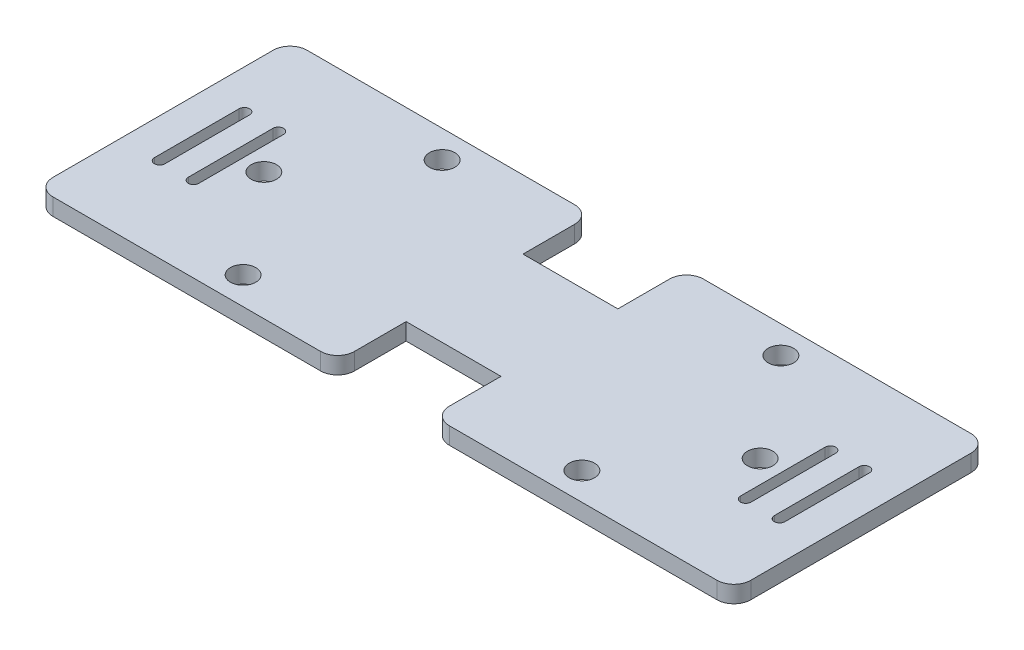
SolidWorks part; units mm, degrees
material "Thornel Mat VMA"
ref_plane "前视基准面" through (0, 0, 0) normal (0, 0, 1) x (1, 0, 0)
ref_plane "上视基准面" through (0, 0, 0) normal (0, 1, 0) x (1, 0, 0)
ref_plane "右视基准面" through (0, 0, 0) normal (1, 0, 0) x (0, 0, -1)
other "Configuration Table"
sketch "草图1" plane through (0, 0, 0) normal (0, 1, 0) x (1, 0, 0)
  line L0 (-5.6, 6.9) -> (-5.6, 13)
  line L1 (-39.2, -15) -> (-7.6, -15)
  line L2 (-41.2, -13) -> (-41.2, 13)
  line L3 (-39.2, 15) -> (-7.6, 15)
  line L4 (41.2, -13) -> (41.2, 13)
  line L5 (-5.6, 6.9) -> (5.6, -6.9) construction
  line L6 (5.6, 6.9) -> (5.6, -6.9) construction
  line L7 (-5.6, -6.9) -> (5.6, -6.9)
  line L9 (-5.6, 6.9) -> (5.6, 6.9)
  line L11 (-5.6, 6.9) -> (-5.6, -6.9) construction
  line L12 (0, 0) -> (41.2, -15) construction
  line L13 (5.6, 6.9) -> (5.6, 13)
  line L14 (-5.6, -6.9) -> (-5.6, -13)
  line L15 (5.6, -6.9) -> (5.6, -13)
  line L16 (7.6, -15) -> (39.2, -15)
  line L17 (7.6, 15) -> (39.2, 15)
  line L18 (0, 0) -> (-41.2, -15) construction
  line L19 (-20, -11.75) -> (20, -11.75) construction
  line L20 (0, 0) -> (0, -11.75) construction
  line L21 (41.2, 0) -> (32.6, 0) construction
  line L22 (-29.3, 0) -> (29.3, 0) construction
  line L23 (32.6, 5) -> (32.6, -5) construction
  line L24 (33.225, 5) -> (33.225, -5)
  line L25 (31.975, 5) -> (31.975, -5)
  line L26 (41.2, 0) -> (36.6, 0) construction
  line L27 (36.6, 5) -> (36.6, -5) construction
  line L28 (37.225, 5) -> (37.225, -5)
  line L29 (35.975, 5) -> (35.975, -5)
  line L30 (-36.6, 5) -> (-36.6, -5) construction
  line L31 (-37.225, 5) -> (-37.225, -5)
  line L32 (-35.975, 5) -> (-35.975, -5)
  line L33 (-32.6, 5) -> (-32.6, -5) construction
  line L34 (-33.225, 5) -> (-33.225, -5)
  line L35 (-31.975, 5) -> (-31.975, -5)
  circle A0 centre (-20, -11.75) radius 1.5
  circle A1 centre (20, -11.75) radius 1.5
  circle A2 centre (20, 11.75) radius 1.5
  circle A3 centre (-20, 11.75) radius 1.5
  circle A4 centre (-29.3, 0) radius 1.5
  circle A5 centre (29.3, 0) radius 1.5
  arc A6 (33.225, 5) -> (31.975, 5) centre (32.6, 5) ccw
  arc A7 (31.975, -5) -> (33.225, -5) centre (32.6, -5) ccw
  arc A8 (37.225, 5) -> (35.975, 5) centre (36.6, 5) ccw
  arc A9 (35.975, -5) -> (37.225, -5) centre (36.6, -5) ccw
  arc A10 (-37.225, 5) -> (-35.975, 5) centre (-36.6, 5) cw
  arc A11 (-35.975, -5) -> (-37.225, -5) centre (-36.6, -5) cw
  arc A12 (-33.225, 5) -> (-31.975, 5) centre (-32.6, 5) cw
  arc A13 (-31.975, -5) -> (-33.225, -5) centre (-32.6, -5) cw
  arc A14 (5.6, -13) -> (7.6, -15) centre (7.6, -13) ccw
  arc A15 (39.2, -15) -> (41.2, -13) centre (39.2, -13) ccw
  arc A16 (39.2, 15) -> (41.2, 13) centre (39.2, 13) cw
  arc A17 (5.6, 13) -> (7.6, 15) centre (7.6, 13) cw
  arc A18 (-5.6, 13) -> (-7.6, 15) centre (-7.6, 13) ccw
  arc A19 (-5.6, -13) -> (-7.6, -15) centre (-7.6, -13) cw
  arc A20 (-39.2, -15) -> (-41.2, -13) centre (-39.2, -13) cw
  arc A21 (-41.2, 13) -> (-39.2, 15) centre (-39.2, 13) cw
  point P0 (0, 0)
  point P6 (0, 0)
  point P33 (32.6, 0)
  point P41 (36.6, 0)
  point P48 (-36.6, 0)
  point P55 (-32.6, 0)
  point P62 (5.6, -15)
  point P68 (41.2, 15)
  point P71 (5.6, 15)
  point P81 (-41.2, 15)
  dimension "D7" = 3
  dimension "D9" = 3
  dimension "D14" = 2
  dimension "D1" = 82.4
  dimension "D2" = 30
  dimension "D3" = 11.2
  dimension "D4" = 13.8
  dimension "D5" = 40
  dimension "D6" = 11.75
  dimension "D8" = 29.3
  dimension "D10" = 8.6
  dimension "D11" = 10
  dimension "D12" = 1.25
  dimension "D13" = 4.6
  dimension "D15" = 40
extrude "凸台-拉伸1" add sketch "草图1" along normal blind 2
